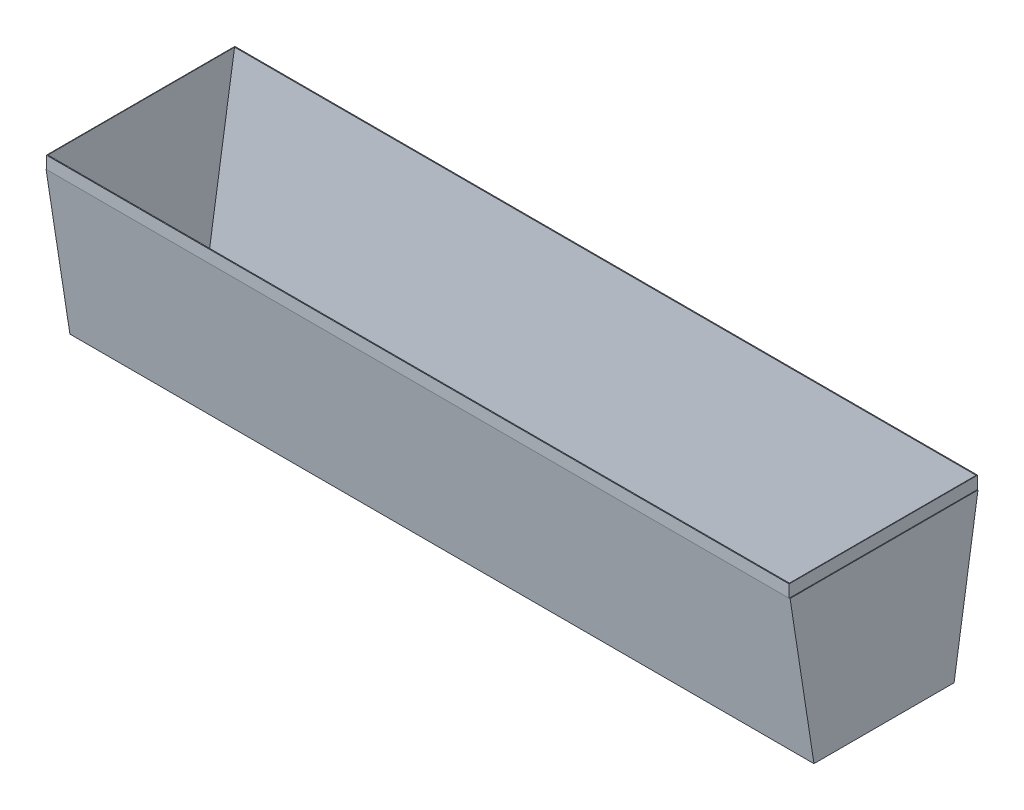
SolidWorks part; units mm, degrees
ref_plane "Front" through (0, 0, 0) normal (0, 0, 1) x (1, 0, 0)
ref_plane "Top" through (0, 0, 0) normal (0, 1, 0) x (1, 0, 0)
ref_plane "Right" through (0, 0, 0) normal (1, 0, 0) x (0, 0, -1)
sketch "Sketch1" plane through (0, 0, 0) normal (1, 0, 0) x (0, 0, -1)
  line L0 (0, 0) -> (113, 0)
  line L2 (141.5, 130) -> (-28.5, 130) construction
  line L4 (56.5, 0) -> (56.5, 130) construction
  line L5 (-28.5, 130) -> (-28.5, 120) construction
  line L6 (-28.5, 120) -> (-18.5, 120) construction
  line L7 (-20.0417, 130) -> (0, 0)
  line L8 (141.5, 130) -> (141.5, 120)
  line L9 (141.5, 120) -> (131.5, 120)
  line L10 (133.0417, 130) -> (113, 0)
  line L11 (-20.0417, 130) -> (133.0417, 130)
  dimension "D1" = 113
  dimension "D2" = 170
  dimension "D3" = 130
  dimension "D4" = 10
  dimension "D5" = 10
  dimension "D6" = 10
  dimension "D7" = 10
  dimension "D8" = 8.4583
  dimension "D9" = 8.4583
extrude "Boss-Extrude1" add sketch "Sketch1" against normal mid plane 600 contours L11 L10 L0 L7
sketch "Sketch2" plane through (0, 130, 0) normal (0, 1, 0) x (1, 0, 0)
  line L28 (308.4583, -28.5) -> (308.4583, 141.5)
  line L29 (-308.4583, -28.5) -> (308.4583, -28.5)
  line L30 (-308.4583, 141.5) -> (-308.4583, -28.5)
  line L31 (308.4583, 141.5) -> (-308.4583, 141.5)
  line L32 (308.4583, -28.5) -> (308.4583, 141.5)
  line L33 (-308.4583, -28.5) -> (308.4583, -28.5)
  line L34 (-308.4583, 141.5) -> (-308.4583, -28.5)
  line L35 (308.4583, 141.5) -> (-308.4583, 141.5)
  dimension "D1" = 8.4583
extrude "Boss-Extrude2" add sketch "Sketch2" along normal mid plane 10
sketch "Sketch3" plane through (-300, 0, 0) normal (-1, 0, 0) x (0, 0, 1)
  line L13 (-131.7889, 135) -> (18.7889, 135)
  line L14 (-141.5, 135) -> (28.5, 135) construction
  line L16 (-1.7153, 2) -> (17.2942, 125.3047)
  line L17 (-111.2847, 2) -> (-1.7153, 2)
  line L18 (-130.2942, 125.3047) -> (-111.2847, 2)
  line L19 (-1.7153, 2) -> (18.7889, 135)
  line L20 (-111.2847, 2) -> (-1.7153, 2)
  line L21 (-131.7889, 135) -> (-111.2847, 2)
  dimension "D1" = 2
extrude "Cut-Extrude1" cut sketch "Sketch3" against normal mid plane 598 from offset 300 offset against normal yes
sketch "Sketch4" plane through (0, 0, -141.5) normal (0, 0, -1) x (-1, 0, 0)
  line L1 (-308.4583, 135) -> (308.4583, 135)
  line L2 (-308.4583, 135) -> (-308.4583, 125)
  line L3 (-308.4583, 125) -> (308.4583, 125)
  line L4 (308.4583, 135) -> (308.4583, 125)
extrude "Cut-Extrude2" cut sketch "Sketch4" against normal blind 9
sketch "Sketch5" plane through (0, 0, 28.5) normal (0, 0, 1) x (1, 0, 0)
  line L1 (-308.4583, 135) -> (308.4583, 135)
  line L2 (-308.4583, 135) -> (-308.4583, 125)
  line L3 (-308.4583, 125) -> (308.4583, 125)
  line L4 (308.4583, 135) -> (308.4583, 125)
extrude "Cut-Extrude3" cut sketch "Sketch5" against normal blind 9
sketch "Sketch6" plane through (-308.4583, 0, 0) normal (-1, 0, 0) x (0, 0, 1)
  line L1 (-132.5, 135) -> (19.5, 135)
  line L2 (-132.5, 135) -> (-132.5, 125)
  line L3 (-132.5, 125) -> (19.5, 125)
  line L4 (19.5, 135) -> (19.5, 125)
extrude "Cut-Extrude4" cut sketch "Sketch6" against normal blind 9
sketch "Sketch7" plane through (308.4583, 0, 0) normal (1, 0, 0) x (0, 0, -1)
  line L1 (-19.5, 135) -> (132.5, 135)
  line L2 (-19.5, 135) -> (-19.5, 125)
  line L3 (-19.5, 125) -> (132.5, 125)
  line L4 (132.5, 135) -> (132.5, 125)
extrude "Cut-Extrude5" cut sketch "Sketch7" against normal blind 9
